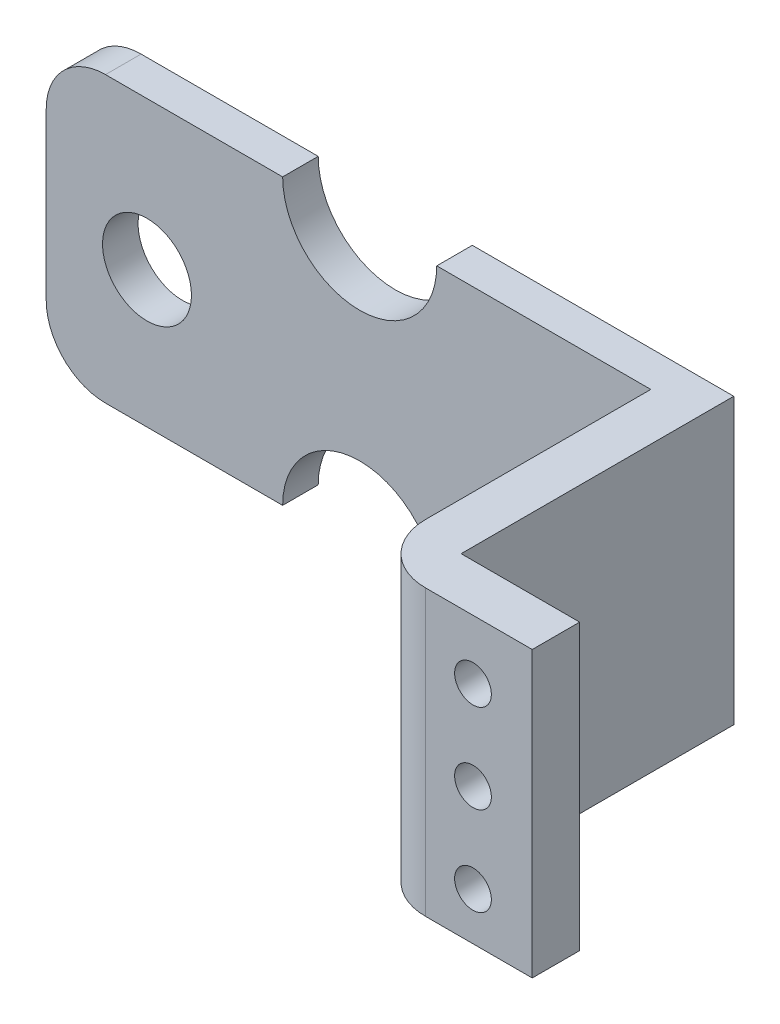
SolidWorks part; units mm, degrees
ref_plane "Front Plane" through (0, 0, 0) normal (0, 0, 1) x (1, 0, 0)
ref_plane "Top Plane" through (0, 0, 0) normal (0, 1, 0) x (1, 0, 0)
ref_plane "Right Plane" through (0, 0, 0) normal (1, 0, 0) x (0, 0, -1)
sketch "Sketch1" plane through (0, 0, 0) normal (0, 0, 1) x (1, 0, 0)
  line L1 (27.5, -12) -> (-27.5, -12)
  line L2 (27.5, -12) -> (27.5, 12)
  line L3 (27.5, 12) -> (-27.5, 12)
  line L4 (-27.5, -12) -> (-27.5, 12)
  line L5 (27.5, -12) -> (-27.5, 12) construction
  line L6 (27.5, 12) -> (-27.5, -12) construction
  circle A0 centre (-19, -0.5) radius 3.75
  circle A1 centre (17, -0.5) radius 3.75
  point P0 (0, 0)
  dimension "D2" = 7.5
  dimension "D3" = 7.5
  dimension "D1" = 24
  dimension "55" = 55
  dimension "D4" = 8.5
  dimension "D5" = 10.5
extrude "Boss-Extrude1" add sketch "Sketch1" along normal blind 3
sketch "Sketch3" plane through (0, 0, 3) normal (0, 0, 1) x (1, 0, 0)
  line L0 (-27.5, -12) -> (27.5, -12) construction
  line L1 (27.5, 12) -> (23.5, 12)
  line L2 (27.5, 12) -> (27.5, -12)
  line L3 (27.5, -12) -> (23.5, -12)
  line L4 (23.5, 12) -> (23.5, -12)
  dimension "D1" = 4
extrude "Boss-Extrude2" add sketch "Sketch3" along normal blind 24
sketch "Sketch4" plane through (27.5, 0, 0) normal (1, 0, 0) x (0, 0, -1)
  line L0 (-27, -12) -> (0, -12) construction
  line L1 (-27, 12) -> (-23, 12)
  line L2 (-27, 12) -> (-27, -12)
  line L3 (-27, -12) -> (-23, -12)
  line L4 (-23, 12) -> (-23, -12)
  dimension "D1" = 4
extrude "Boss-Extrude3" add sketch "Sketch4" along normal blind 10
sketch "Sketch5" plane through (0, 0, 27) normal (0, 0, 1) x (1, 0, 0)
  line L0 (37.5, 12) -> (23.5, 12) construction
  line L1 (37.5, 12) -> (37.5, -12) construction
  circle A0 centre (32.5, 7) radius 1.55
  circle A1 centre (32.5, -0.5) radius 1.55
  circle A2 centre (32.5, -8) radius 1.55
  dimension "D1" = 3.1
  dimension "D2" = 7.5
  dimension "D3" = 7.5
  dimension "D4" = 5
  dimension "D5" = 5
extrude "Cut-Extrude1" cut sketch "Sketch5" against normal blind 10
sketch "Sketch6" plane through (0, 0, 3) normal (0, 0, 1) x (1, 0, 0)
  line L0 (23.5, 12) -> (-27.5, 12) construction
  line L1 (-28.9812, 0) -> (23.5, 0) construction
  line L2 (23.5, 12) -> (23.5, -12) construction
  circle A0 centre (-1.0566, 12) radius 6.5
  circle A1 centre (-1.0566, -12) radius 6.5
  dimension "D1" = 13
extrude "Cut-Extrude2" cut sketch "Sketch6" against normal up to next
fillet "Fillet1" radius 5 3 edges at (23.5, 0, 27) (-27.5, -12, 1.5) (-27.5, 12, 1.5)
